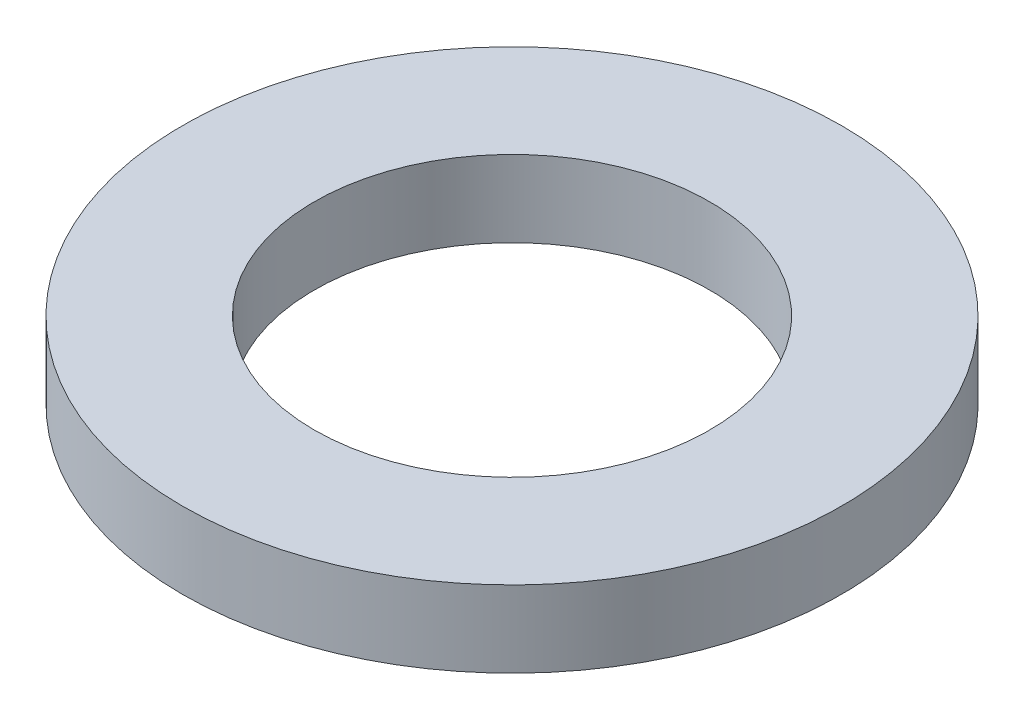
SolidWorks part; units mm, degrees
ref_plane "前视基准面" through (0, 0, 0) normal (0, 0, 1) x (1, 0, 0)
ref_plane "上视基准面" through (0, 0, 0) normal (0, 1, 0) x (1, 0, 0)
ref_plane "右视基准面" through (0, 0, 0) normal (1, 0, 0) x (0, 0, -1)
other "Configuration Table"
sketch "草图1" plane through (0, 0, 0) normal (0, 1, 0) x (1, 0, 0)
  circle A0 centre (0, 0) radius 25
  circle A1 centre (0, 0) radius 15
  dimension "D1" = 50
  dimension "D2" = 30
extrude "凸台-拉伸1" add sketch "草图1" along normal blind 5.8
